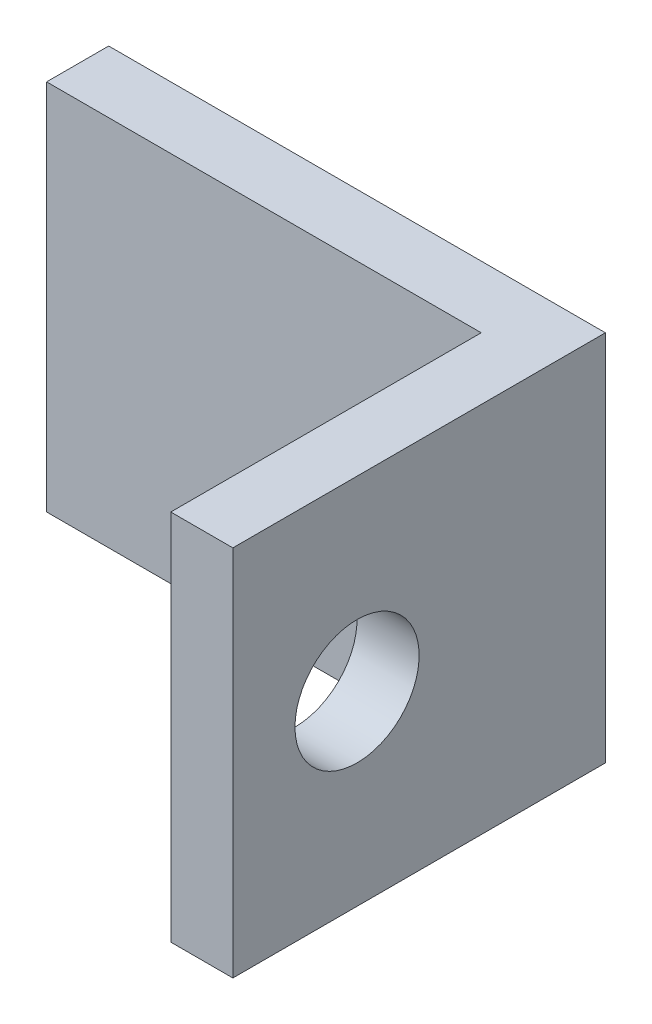
SolidWorks part; units mm, degrees
material "1060 Alloy"
ref_plane "Front" through (0, 0, 0) normal (0, 0, 1) x (1, 0, 0)
ref_plane "Top" through (0, 0, 0) normal (0, 1, 0) x (1, 0, 0)
ref_plane "Right" through (0, 0, 0) normal (1, 0, 0) x (0, 0, -1)
sketch "Sketch1" plane through (0, 0, 0) normal (0, 1, 0) x (1, 0, 0)
  line L0 (0, 0) -> (12.7, 0)
  line L1 (12.7, 0) -> (12.7, -9.525)
  line L2 (12.7, -9.525) -> (11.1125, -9.525)
  line L3 (11.1125, -9.525) -> (11.1125, -1.5875)
  line L4 (11.1125, -1.5875) -> (0, -1.5875)
  line L5 (0, -1.5875) -> (0, 0)
  dimension "D1" = 1.5875
  dimension "D2" = 1.5875
  dimension "D3" = 12.7
  dimension "D4" = 9.525
extrude "Boss-Extrude1" add sketch "Sketch1" along normal blind 9.525
hole_wizard "1/8 (0.125) Diameter Hole1" positions "Sketch2" profile "Sketch3" hole size "1/8" standard "ANSI Inch" end condition through all
sketch "Sketch2" plane through (11.1125, 0, 0) normal (-1, 0, 0) x (0, 0, 1)
  line L0 (9.525, 9.525) -> (9.525, 0) construction
  point P0 (6.35, 4.7625)
  point P7 (9.525, 4.7625)
  dimension "D1" = 3.175
sketch "Sketch3" plane through (11.1125, 4.7625, 6.35) normal (0, 1, 0) x (0, 0, 1)
  line L0 (0, 0) -> (0, 1.5875)
  line L1 (0, 1.5875) -> (1.5875, 1.5875)
  line L2 (1.5875, 1.5875) -> (1.5875, 0)
  line L5 (1.5875, 0) -> (0, 0)
  line L11 (0, -6.35) -> (0, 107.95) construction
  dimension "Thru Hole Dia." = 3.175
  dimension "Thru Hole Depth" = 1.5875
